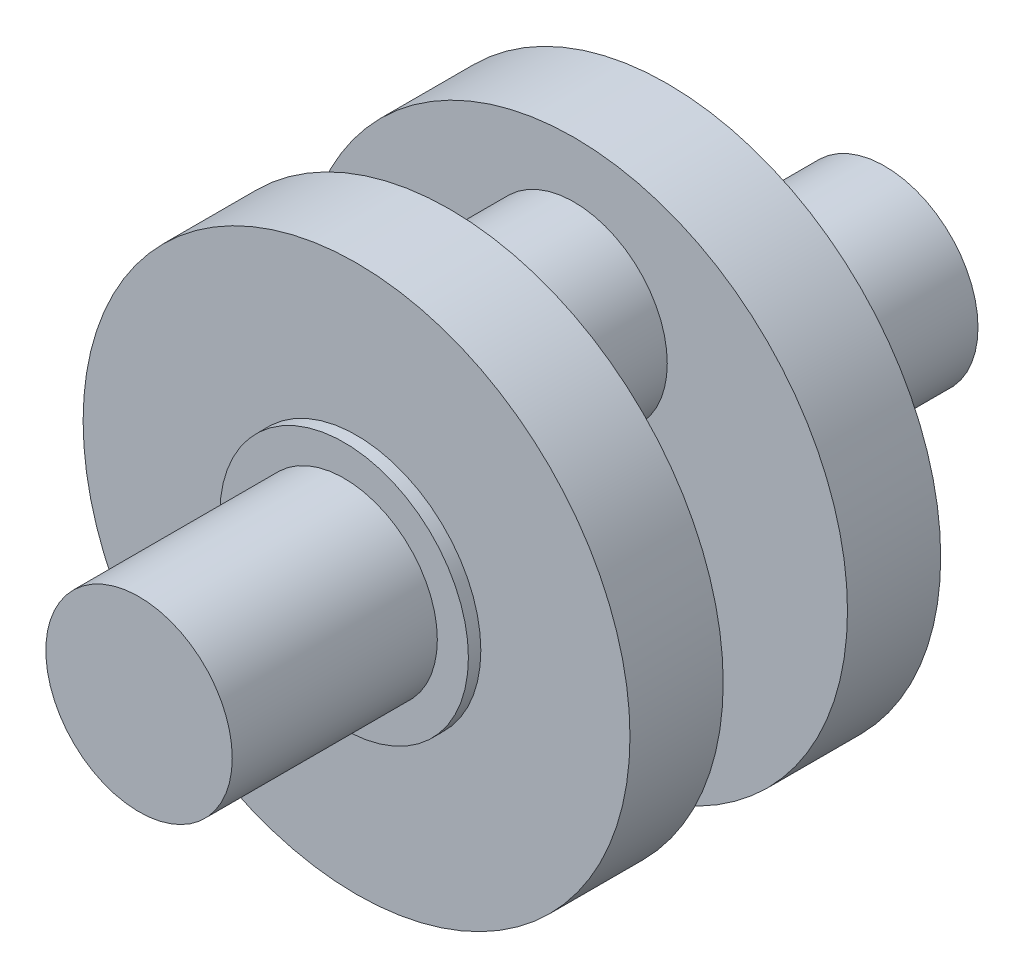
SolidWorks part; units mm, degrees
ref_plane "Płaszczyzna przednia" through (0, 0, 0) normal (0, 0, 1) x (1, 0, 0)
ref_plane "Płaszczyzna górna" through (0, 0, 0) normal (0, 1, 0) x (1, 0, 0)
ref_plane "Płaszczyzna prawa" through (0, 0, 0) normal (1, 0, 0) x (0, 0, -1)
sketch "Szkic3" plane through (0, 0, 0) normal (0, 0, 1) x (1, 0, 0)
  circle A0 centre (0, 0) radius 15
  dimension "D1" = 30
extrude "Dodanie-wyciągnięcie2" add sketch "Szkic3" along normal blind 33
sketch "Szkic4" plane through (0, 0, 0) normal (0, 0, 1) x (1, 0, 0)
  circle A0 centre (0, 0) radius 20
  dimension "D1" = 40
extrude "Dodanie-wyciągnięcie3" add sketch "Szkic4" against normal blind 2
sketch "Szkic5" plane through (0, 0, 0) normal (0, 0, 1) x (1, 0, 0)
  circle A0 centre (0, 0) radius 44
  point P3 (0, 0)
  dimension "D1" = 88
extrude "Dodanie-wyciągnięcie4" add sketch "Szkic5" against normal blind 15 from surface at -2 starting at face at (20, 0, -2)
sketch "Szkic6" plane through (0, 0, 0) normal (0, 0, 1) x (1, 0, 0)
  circle A0 centre (0, 20) radius 15
  point P2 (0, 0)
  point P5 (0.5136, 19.1325)
  dimension "D1" = 30
  dimension "D2" = 20
extrude "Dodanie-wyciągnięcie5" add sketch "Szkic6" against normal blind 10 from surface at -17 starting at face at (44, 0, -17)
mirror "Lustro1" about plane through (0, 20, -27) normal (0, 0, 1) of bodies 105
